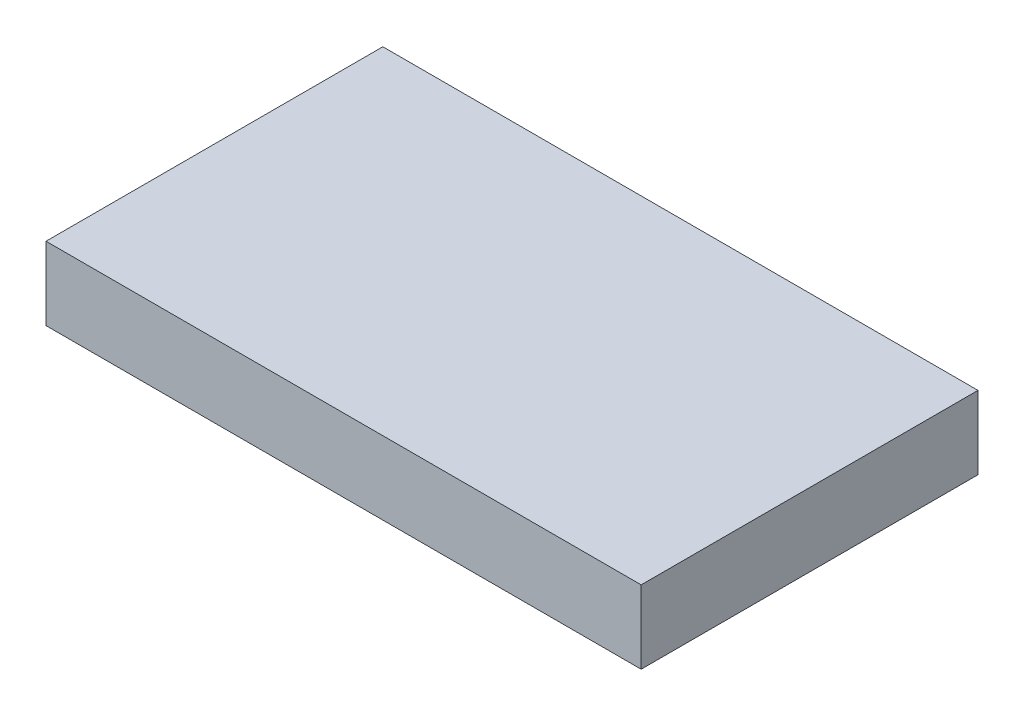
SolidWorks part; units mm, degrees
ref_plane "Front Plane" through (0, 0, 0) normal (0, 0, 1) x (1, 0, 0)
ref_plane "Top Plane" through (0, 0, 0) normal (0, 1, 0) x (1, 0, 0)
ref_plane "Right Plane" through (0, 0, 0) normal (1, 0, 0) x (0, 0, -1)
sketch "Sketch1" plane through (0, 0, 0) normal (0, 1, 0) x (1, 0, 0)
  line L1 (241, -136.4) -> (-241, -136.4)
  line L2 (241, -136.4) -> (241, 136.4)
  line L3 (241, 136.4) -> (-241, 136.4)
  line L4 (-241, -136.4) -> (-241, 136.4)
  line L5 (241, -136.4) -> (-241, 136.4) construction
  line L6 (241, 136.4) -> (-241, -136.4) construction
  point P0 (0, 0)
  dimension "D1" = 272.8
  dimension "D2" = 482
extrude "Boss-Extrude1" add sketch "Sketch1" along normal blind 59.2
